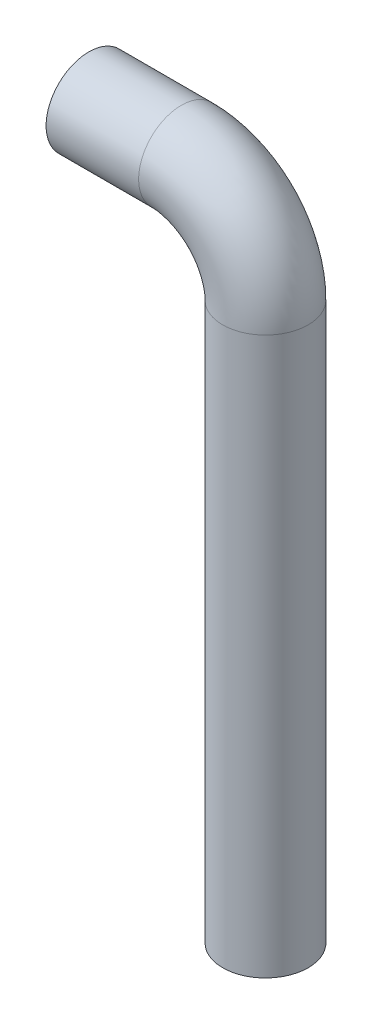
SolidWorks part; units mm, degrees
material "1060 Alloy"
ref_plane "Front Plane" through (0, 0, 0) normal (0, 0, 1) x (1, 0, 0)
ref_plane "Top Plane" through (0, 0, 0) normal (0, 1, 0) x (1, 0, 0)
ref_plane "Right Plane" through (0, 0, 0) normal (1, 0, 0) x (0, 0, -1)
sketch "Sketch1" plane through (0, 0, 0) normal (0, 0, 1) x (1, 0, 0)
  line L0 (0, 0) -> (110, 0)
  line L1 (210, -100) -> (210, -762)
  arc A0 (110, 0) -> (210, -100) centre (110, -100) cw
  point P6 (210, 0)
  dimension "D3" = 100
  dimension "D1" = 210
  dimension "D2" = 762
sketch "Sketch2" plane through (0, 0, 0) normal (1, 0, 0) x (0, 0, -1)
  circle A0 centre (0, 0) radius 29.86
  circle A1 centre (0, 0) radius 50.8
  dimension "D1" = 59.72
  dimension "D2" = 101.6
sweep "Sweep1" add profiles "Sketch2" path "Sketch1"
